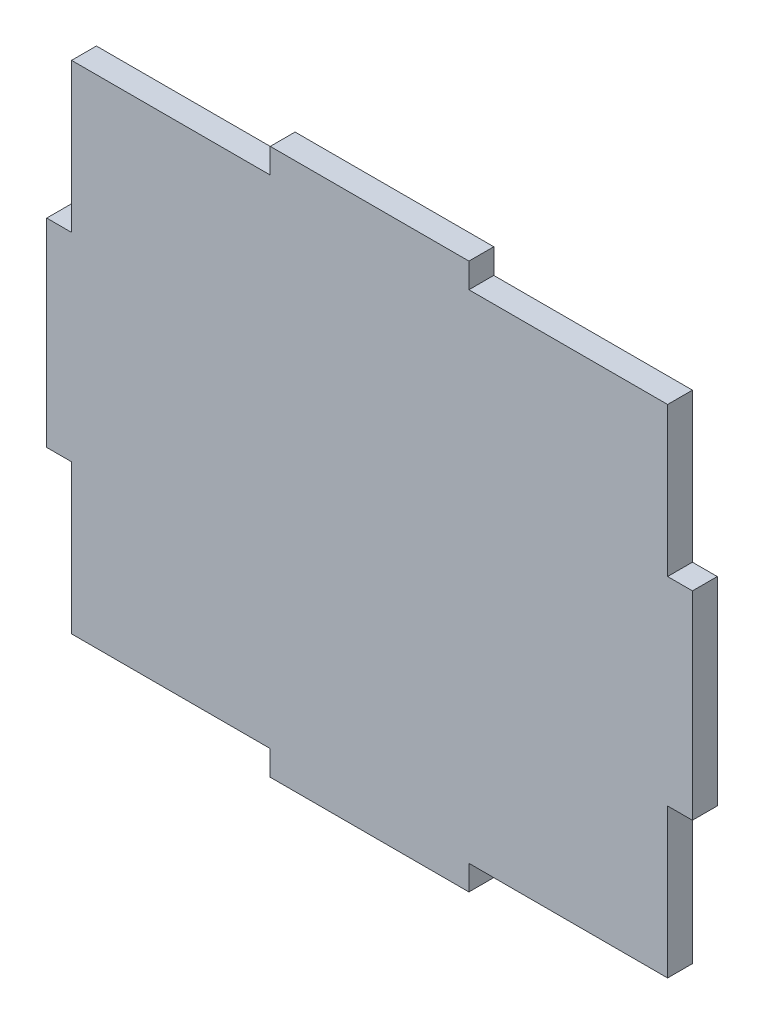
SolidWorks part; units mm, degrees
material "Maple"
ref_plane "Front Plane" through (0, 0, 0) normal (0, 0, 1) x (1, 0, 0)
ref_plane "Top Plane" through (0, 0, 0) normal (0, 1, 0) x (1, 0, 0)
ref_plane "Right Plane" through (0, 0, 0) normal (1, 0, 0) x (0, 0, -1)
sketch "Sketch1" plane through (0, 0, 0) normal (0, 0, 1) x (1, 0, 0)
  line L0 (-30, -25) -> (-30, 25) construction
  line L1 (-32.5, -27.5) -> (32.5, -27.5) construction
  line L2 (-32.5, -27.5) -> (-32.5, 27.5) construction
  line L3 (-32.5, 27.5) -> (32.5, 27.5) construction
  line L4 (32.5, -27.5) -> (32.5, 27.5) construction
  line L5 (-32.5, -27.5) -> (32.5, 27.5) construction
  line L6 (-32.5, 27.5) -> (32.5, -27.5) construction
  line L7 (-30, 25) -> (30, 25) construction
  line L8 (30, -25) -> (30, 25) construction
  line L9 (-30, -25) -> (30, -25) construction
  line L10 (-32.5, 10) -> (-32.5, -10)
  line L11 (-32.5, -10) -> (-30, -10)
  line L12 (-30, -10) -> (-30, -25)
  line L13 (-30, -25) -> (-10, -25)
  line L14 (-10, -25) -> (-10, -27.5)
  line L15 (-10, -27.5) -> (10, -27.5)
  line L16 (-9.4058, 0) -> (8.9806, 0) construction
  line L17 (0, -5.5705) -> (0, 7.9444) construction
  line L18 (-10, 27.5) -> (10, 27.5)
  line L19 (-10, 25) -> (-10, 27.5)
  line L20 (-30, 25) -> (-10, 25)
  line L21 (-30, 10) -> (-30, 25)
  line L22 (-32.5, 10) -> (-30, 10)
  line L23 (10, -25) -> (10, -27.5)
  line L24 (30, -25) -> (10, -25)
  line L25 (30, -10) -> (30, -25)
  line L26 (32.5, -10) -> (30, -10)
  line L27 (32.5, 10) -> (32.5, -10)
  line L28 (32.5, 10) -> (30, 10)
  line L29 (30, 10) -> (30, 25)
  line L30 (30, 25) -> (10, 25)
  line L31 (10, 25) -> (10, 27.5)
  point P0 (0, 0)
  point P25 (-32.5, 0)
  point P26 (0, -27.5)
  point P33 (0, 27.5)
  dimension "D1" = 65
  dimension "D2" = 55
  dimension "D4" = 20
  dimension "D3" = 2.5
extrude "Boss-Extrude1" add sketch "Sketch1" along normal mid plane 2.5
